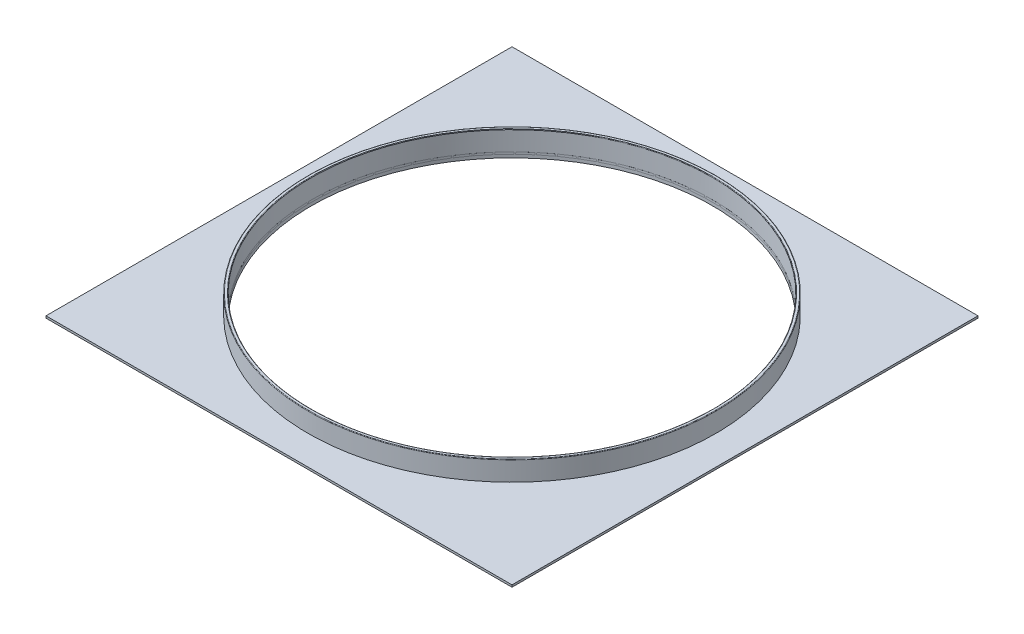
SolidWorks part; units mm, degrees
ref_plane "Front Plane" through (0, 0, 0) normal (0, 0, 1) x (1, 0, 0)
ref_plane "Top Plane" through (0, 0, 0) normal (0, 1, 0) x (1, 0, 0)
ref_plane "Right Plane" through (0, 0, 0) normal (1, 0, 0) x (0, 0, -1)
sketch "Sketch1" plane through (0, 0, 0) normal (1, 0, 0) x (0, 0, -1)
  line L0 (306.3875, 0) -> (349.25, 0)
  line L1 (349.25, 0) -> (349.25, 4.7625)
  line L2 (349.25, 4.7625) -> (311.15, 4.7625)
  line L3 (311.15, 4.7625) -> (311.15, 38.1)
  line L4 (311.15, 38.1) -> (306.3875, 38.1)
  line L5 (0, 38.1) -> (0, 0) construction
  line L6 (0, 50.5185) -> (0, -6.35) construction
  line L7 (306.3875, 38.1) -> (306.3875, 0)
  dimension "Flange Thk" = 4.7625
  dimension "Depth" = 38.1
  dimension "Flange Ht" = 38.1
  dimension "D1" = 4.7625
  dimension "D2" = 6.35
  dimension "ID" = 612.775
revolve "Revolve1" add sketch "Sketch1" angle 360 about L5
sketch "Sketch2" plane through (0, 38.1, 0) normal (0, 1, 0) x (1, 0, 0)
  line L0 (12.7, 0) -> (306.3875, 0) construction
  circle A0 centre (0, 0) radius 115.8875
  circle A1 centre (0, 0) radius 306.3875 construction
  circle A2 centre (0, 0) radius 349.25 construction
  dimension "D1" = 293.6875
  dimension "ID" = 231.775
fillet "Fillet3" radius 0.7938 2 edges at (0, 0, 349.25) (0, 4.7625, 349.25)
fillet "Fillet4" radius 0.7938 3 edges at (0, 38.1, 311.15) (0, 4.7625, 311.15) (0, 38.1, 306.3875)
sketch "Sketch3" plane through (0, 4.7625, 0) normal (0, 1, 0) x (-1, 0, 0)
  circle A0 centre (0, -328.6125) radius 5.5563
  circle A1 centre (0, 0) radius 328.6125 construction
  dimension "mounting hole size" = 11.1125
  dimension "BoltCircle" = 657.225
extrude "Cut-Extrude1" cut sketch "Sketch3" against normal through all
pattern_circular "CirPattern1" count 12 over 360 about axis through (0, 0, 0) along (0, 1, 0) of "Cut-Extrude1"
sketch "Sketch4" plane through (0, 4.7625, 0) normal (0, 1, 0) x (1, 0, 0)
  line L1 (-355.6, 355.6) -> (355.6, 355.6)
  line L2 (-355.6, 355.6) -> (-355.6, -355.6)
  line L3 (-355.6, -355.6) -> (355.6, -355.6)
  line L4 (355.6, 355.6) -> (355.6, -355.6)
  line L5 (-355.6, 355.6) -> (355.6, -355.6) construction
  line L6 (-355.6, -355.6) -> (355.6, 355.6) construction
  circle A0 centre (0, 0) radius 306.3875 construction
  circle A1 centre (0, 0) radius 306.3875
  point P0 (0, 0)
  dimension "D1" = 711.2
  dimension "D2" = 711.2
extrude "Boss-Extrude1" add sketch "Sketch4" along normal blind 3.175 separate body
equation "\"D1@Fillet3\" = \"Flange Thk@Sketch1\"/6"
equation "\"D1@Fillet4\" = \"Flange Thk@Sketch1\"/6"
equation "\"D1@Sketch1\" = \"Flange Thk@Sketch1\""
